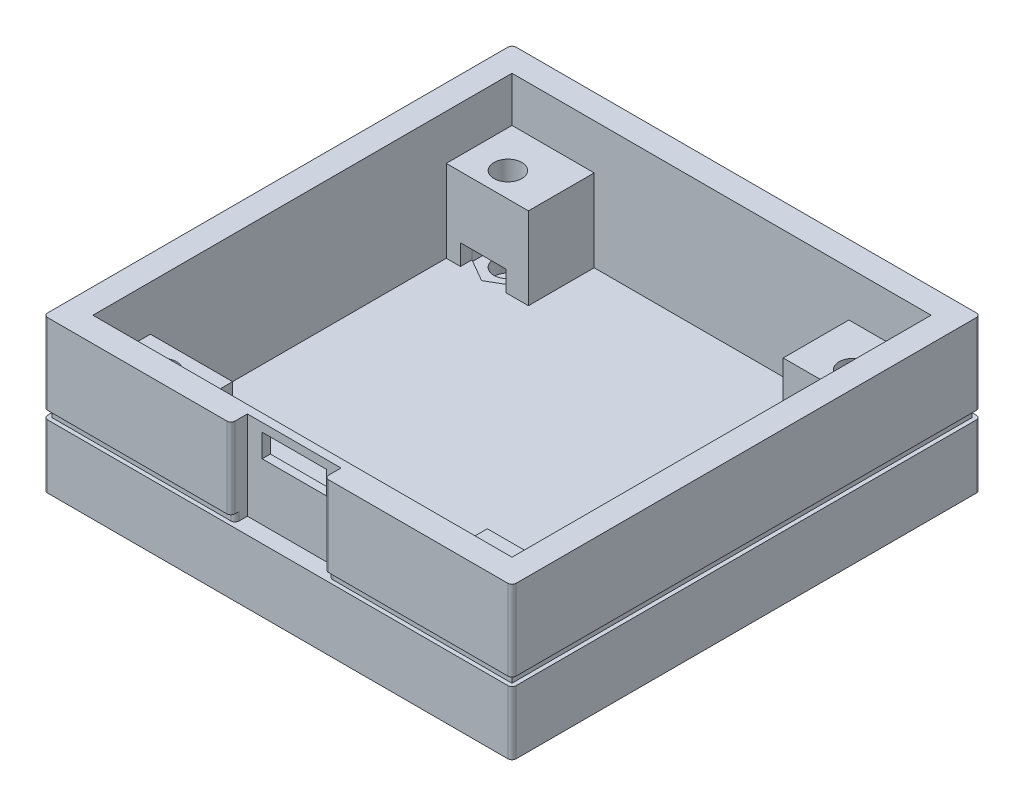
SolidWorks part; units mm, degrees
ref_plane "Plan de face" through (0, 0, 0) normal (0, 0, 1) x (1, 0, 0)
ref_plane "Plan de dessus" through (0, 0, 0) normal (0, 1, 0) x (1, 0, 0)
ref_plane "Plan de droite" through (0, 0, 0) normal (1, 0, 0) x (0, 0, -1)
sketch "Esquisse1" plane through (0, 0, 0) normal (0, 1, 0) x (1, 0, 0)
  line L1 (-30.0101, 36.8942) -> (26.9899, 36.8942)
  line L2 (-30.0101, 36.8942) -> (-30.0101, -20.1058)
  line L3 (-30.0101, -20.1058) -> (26.9899, -20.1058)
  line L4 (26.9899, 36.8942) -> (26.9899, -20.1058)
extrude "Boss.-Extru.1" add sketch "Esquisse1" along normal blind 18.5 contours L2 L3 L4 L1
sketch "Esquisse2" plane through (0, 18.5, 0) normal (0, 1, 0) x (1, 0, 0)
  line L0 (-30.0101, 36.8942) -> (26.9899, 36.8942) construction
  line L1 (-27.0101, 33.8942) -> (23.9899, 33.8942)
  line L2 (-27.0101, 33.8942) -> (-27.0101, -17.1058)
  line L3 (-27.0101, -17.1058) -> (23.9899, -17.1058)
  line L4 (23.9899, 33.8942) -> (23.9899, -17.1058)
  line L5 (-30.0101, 36.8942) -> (-30.0101, -20.1058) construction
  line L6 (26.9899, 36.8942) -> (26.9899, -20.1058) construction
  line L7 (-30.0101, -20.1058) -> (26.9899, -20.1058) construction
  dimension "D1" = 3
  dimension "D2" = 3
  dimension "D3" = 3
  dimension "D4" = 3
extrude "Enlèv. mat.-Extru.1" cut sketch "Esquisse2" against normal blind 15.5 contours L2 L3 L4 L1
sketch "Esquisse4" plane through (0, 3, 0) normal (0, 1, 0) x (1, 0, 0)
  line L1 (-17.0101, 25.8942) -> (-27.0101, 25.8942)
  line L2 (-17.0101, 25.8942) -> (-17.0101, 33.8942)
  line L3 (-17.0101, 33.8942) -> (-27.0101, 33.8942)
  line L4 (-27.0101, 25.8942) -> (-27.0101, 33.8942)
extrude "Boss.-Extru.2" add sketch "Esquisse4" along normal blind 10
sketch "Esquisse5" plane through (0, 3, 0) normal (0, 1, 0) x (1, 0, 0)
  line L1 (23.9899, 33.8942) -> (13.9899, 33.8942)
  line L2 (23.9899, 33.8942) -> (23.9899, 25.8942)
  line L3 (23.9899, 25.8942) -> (13.9899, 25.8942)
  line L4 (13.9899, 33.8942) -> (13.9899, 25.8942)
extrude "Boss.-Extru.3" add sketch "Esquisse5" along normal blind 10
sketch "Esquisse6" plane through (0, 3, 0) normal (0, 1, 0) x (1, 0, 0)
  line L1 (23.9899, -17.1058) -> (13.9899, -17.1058)
  line L2 (23.9899, -17.1058) -> (23.9899, -10.1058)
  line L3 (23.9899, -10.1058) -> (13.9899, -10.1058)
  line L4 (13.9899, -17.1058) -> (13.9899, -10.1058)
extrude "Boss.-Extru.4" add sketch "Esquisse6" along normal blind 10
sketch "Esquisse7" plane through (0, 3, 0) normal (0, 1, 0) x (1, 0, 0)
  line L1 (-17.0101, -10.1058) -> (-27.0101, -10.1058)
  line L2 (-17.0101, -10.1058) -> (-17.0101, -17.1058)
  line L3 (-17.0101, -17.1058) -> (-27.0101, -17.1058)
  line L4 (-27.0101, -10.1058) -> (-27.0101, -17.1058)
extrude "Boss.-Extru.5" add sketch "Esquisse7" along normal blind 10
sketch "Esquisse8" plane through (0, 13, 0) normal (0, 1, 0) x (1, 0, 0)
  line L0 (13.9899, -17.1058) -> (23.9899, -17.1058) construction
  line L2 (23.9899, -17.1058) -> (23.9899, -10.1058) construction
  circle A0 centre (19.4899, -13.1058) radius 1.7
  dimension "D1" = 4
  dimension "D2" = 4.5
extrude "Enlèv. mat.-Extru.2" cut sketch "Esquisse8" against normal blind 12
sketch "Esquisse9" plane through (0, 13, 0) normal (0, 1, 0) x (1, 0, 0)
  line L0 (-27.0101, -17.1058) -> (-17.0101, -17.1058) construction
  line L1 (-27.0101, -10.1058) -> (-27.0101, -17.1058) construction
  circle A0 centre (-22.5101, -13.1058) radius 1.7
  dimension "D1" = 4
  dimension "D2" = 4.5
extrude "Enlèv. mat.-Extru.3" cut sketch "Esquisse9" against normal blind 12
sketch "Esquisse16" plane through (0, 13, 0) normal (0, 1, 0) x (1, 0, 0)
  line L0 (-17.0101, 33.8942) -> (-27.0101, 33.8942) construction
  line L1 (-27.0101, 33.8942) -> (-27.0101, 25.8942) construction
  circle A0 centre (-22.5101, 28.8942) radius 1.7
  dimension "D1" = 5
  dimension "D2" = 4.5
extrude "Enlèv. mat.-Extru.9" cut sketch "Esquisse16" against normal blind 12 contours A0
sketch "Esquisse17" plane through (0, 13, 0) normal (0, 1, 0) x (1, 0, 0)
  line L0 (23.9899, 33.8942) -> (13.9899, 33.8942) construction
  line L1 (23.9899, 25.8942) -> (23.9899, 33.8942) construction
  circle A0 centre (19.4899, 28.8942) radius 1.7
  dimension "D1" = 5
  dimension "D2" = 4.5
extrude "Enlèv. mat.-Extru.10" cut sketch "Esquisse17" against normal blind 12
sketch "Esquisse21" plane through (0, 0, 20.1058) normal (0, 0, 1) x (1, 0, 0)
  line L0 (-30.0101, 0) -> (26.9899, 0) construction
  line L1 (-5.4101, 17.47) -> (2.3899, 17.47)
  line L2 (-5.4101, 17.47) -> (-5.4101, 14.67)
  line L3 (-5.4101, 14.67) -> (2.3899, 14.67)
  line L4 (2.3899, 17.47) -> (2.3899, 14.67)
  line L5 (-30.0101, 18.5) -> (-30.0101, 0) construction
  line L7 (26.9899, 18.5) -> (26.9899, 0) construction
  dimension "D1" = 14.67
  dimension "D2" = 24.6
  dimension "D3" = 24.6
extrude "Enlèv. mat.-Extru.14" cut sketch "Esquisse21" against normal blind 3
sketch "Esquisse23" plane through (0, 0, -25.8942) normal (0, 0, 1) x (1, 0, 0)
  line L0 (13.9899, 13) -> (13.9899, 3) construction
  line L5 (22.2599, 5.5) -> (16.7199, 5.5)
  line L6 (22.2599, 5.5) -> (22.2599, 3)
  line L7 (22.2599, 3) -> (16.7199, 3)
  line L8 (16.7199, 5.5) -> (16.7199, 3)
  line L9 (23.9899, 13) -> (23.9899, 3) construction
  dimension "D1" = 2.73
  dimension "D2" = 1.73
sketch "Esquisse24" plane through (0, 13, 0) normal (0, 1, 0) x (1, 0, 0)
  line L1 (19.4899, 25.6942) -> (22.2612, 27.2942)
  line L2 (22.2612, 27.2942) -> (22.2612, 30.4942)
  line L3 (22.2612, 30.4942) -> (19.4899, 32.0942)
  line L4 (19.4899, 32.0942) -> (16.7186, 30.4942)
  line L5 (16.7186, 30.4942) -> (16.7186, 27.2942)
  line L6 (16.7186, 27.2942) -> (19.4899, 25.6942)
  circle A0 centre (19.4899, 28.8942) radius 2.7713 construction
  circle A1 centre (19.4899, 28.8942) radius 1.7 construction
  dimension "D1" = 0
extrude "Enlèv. mat.-Extru.18" cut sketch "Esquisse24" against normal blind 2.7 from offset 7.5 contours L1 L2 L3 L4 L5 L6 offset against normal yes
sketch "Esquisse25" plane through (0, 13, 0) normal (0, 1, 0) x (1, 0, 0)
  line L1 (16.7186, -11.5058) -> (16.7186, -14.7058)
  line L2 (16.7186, -14.7058) -> (19.4899, -16.3058)
  line L3 (19.4899, -16.3058) -> (22.2612, -14.7058)
  line L4 (22.2612, -14.7058) -> (22.2612, -11.5058)
  line L5 (22.2612, -11.5058) -> (19.4899, -9.9058)
  line L6 (19.4899, -9.9058) -> (16.7186, -11.5058)
  circle A0 centre (19.4899, -13.1058) radius 2.7713 construction
  circle A1 centre (19.4899, -13.1058) radius 1.7 construction
  dimension "D1" = 0
extrude "Enlèv. mat.-Extru.20" cut sketch "Esquisse25" against normal blind 2.7 from offset 7.5 offset against normal yes
sketch "Esquisse26" plane through (0, 0, 10.1058) normal (0, 0, -1) x (-1, 0, 0)
  line L0 (-13.9899, 13) -> (-13.9899, 3) construction
  line L1 (-22.2599, 5.5) -> (-16.7199, 5.5)
  line L2 (-22.2599, 5.5) -> (-22.2599, 3)
  line L3 (-22.2599, 3) -> (-16.7199, 3)
  line L4 (-16.7199, 5.5) -> (-16.7199, 3)
  line L5 (-23.9899, 13) -> (-23.9899, 3) construction
  dimension "D1" = 2.73
  dimension "D2" = 1.73
extrude "Enlèv. mat.-Extru.21" cut sketch "Esquisse26" against normal blind 2.848
sketch "Esquisse27" plane through (0, 13, 0) normal (0, 1, 0) x (1, 0, 0)
  line L1 (-19.7388, 27.2942) -> (-19.7388, 30.4942)
  line L2 (-19.7388, 30.4942) -> (-22.5101, 32.0942)
  line L3 (-22.5101, 32.0942) -> (-25.2814, 30.4942)
  line L4 (-25.2814, 30.4942) -> (-25.2814, 27.2942)
  line L5 (-25.2814, 27.2942) -> (-22.5101, 25.6942)
  line L6 (-22.5101, 25.6942) -> (-19.7388, 27.2942)
  circle A0 centre (-22.5101, 28.8942) radius 2.7713 construction
  circle A1 centre (-22.5101, 28.8942) radius 1.7 construction
  dimension "D1" = 0
  dimension "D2" = 0
extrude "Enlèv. mat.-Extru.22" cut sketch "Esquisse27" against normal blind 2.7 from offset 7.5 contours L4 L5 L6 L1 L2 L3 offset against normal yes
sketch "Esquisse29" plane through (0, 13, 0) normal (0, 1, 0) x (1, 0, 0)
  line L1 (-19.7388, -11.5058) -> (-22.5101, -9.9058)
  line L2 (-22.5101, -9.9058) -> (-25.2814, -11.5058)
  line L3 (-25.2814, -11.5058) -> (-25.2814, -14.7058)
  line L4 (-25.2814, -14.7058) -> (-22.5101, -16.3058)
  line L5 (-22.5101, -16.3058) -> (-19.7388, -14.7058)
  line L6 (-19.7388, -14.7058) -> (-19.7388, -11.5058)
  circle A0 centre (-22.5101, -13.1058) radius 2.7713 construction
  circle A1 centre (-22.5101, -13.1058) radius 1.7 construction
  dimension "D1" = 0
extrude "Enlèv. mat.-Extru.24" cut sketch "Esquisse29" against normal blind 2.7 from offset 7.5 offset against normal yes
sketch "Esquisse30" plane through (0, 0, 10.1058) normal (0, 0, -1) x (-1, 0, 0)
  line L0 (17.0101, 13) -> (17.0101, 3) construction
  line L1 (25.2801, 5.5) -> (19.7401, 5.5)
  line L2 (25.2801, 5.5) -> (25.2801, 3)
  line L3 (25.2801, 3) -> (19.7401, 3)
  line L4 (19.7401, 5.5) -> (19.7401, 3)
  line L5 (27.0101, 13) -> (27.0101, 3) construction
  dimension "D1" = 2.73
  dimension "D2" = 1.73
extrude "Enlèv. mat.-Extru.26" cut sketch "Esquisse23" against normal blind 2 contours L5 L8 L7 L6
sketch "Esquisse31" plane through (0, 0, -25.8942) normal (0, 0, 1) x (1, 0, 0)
  line L0 (-27.0101, 13) -> (-27.0101, 3) construction
  line L1 (-25.2801, 5.5) -> (-19.7401, 5.5)
  line L2 (-25.2801, 5.5) -> (-25.2801, 3)
  line L3 (-25.2801, 3) -> (-19.7401, 3)
  line L4 (-19.7401, 5.5) -> (-19.7401, 3)
  line L6 (-17.0101, 13) -> (-17.0101, 3) construction
  dimension "D1" = 1.73
  dimension "D2" = 2.73
extrude "Enlèv. mat.-Extru.27" cut sketch "Esquisse31" against normal blind 2 contours L1 L4 L3 L2
extrude "Enlèv. mat.-Extru.28" cut sketch "Esquisse30" against normal blind 2 contours L1 L4 L3 L2
sketch "Esquisse32" plane through (-30.0101, 0, 0) normal (-1, 0, 0) x (0, 0, 1)
  line L0 (20.1058, 18.5) -> (20.1058, 0) construction
  line L1 (20.1058, 8.72) -> (-36.8942, 8.72)
  line L2 (20.1058, 8.72) -> (20.1058, 7.72)
  line L3 (20.1058, 7.72) -> (-36.8942, 7.72)
  line L4 (-36.8942, 8.72) -> (-36.8942, 7.72)
  line L5 (-36.8942, 18.5) -> (-36.8942, 0) construction
sketch "Esquisse33" plane through (0, 0, 20.1058) normal (0, 0, 1) x (1, 0, 0)
  line L0 (26.9899, 18.5) -> (26.9899, 0) construction
  line L1 (-30.0101, 8.72) -> (26.9899, 8.72)
  line L2 (-30.0101, 8.72) -> (-30.0101, 7.72)
  line L3 (-30.0101, 7.72) -> (26.9899, 7.72)
  line L4 (26.9899, 8.72) -> (26.9899, 7.72)
extrude "Enlèv. mat.-Extru.29" cut sketch "Esquisse32" against normal blind 0.5
extrude "Enlèv. mat.-Extru.30" cut sketch "Esquisse33" against normal blind 0.5 contours L1 L4 L3 L2
sketch "Esquisse34" plane through (26.9899, 0, 0) normal (1, 0, 0) x (0, 0, -1)
  line L0 (36.8942, 18.5) -> (36.8942, 0) construction
  line L1 (-20.1058, 7.72) -> (36.8942, 7.72)
  line L2 (-20.1058, 7.72) -> (-20.1058, 8.72)
  line L3 (-20.1058, 8.72) -> (36.8942, 8.72)
  line L4 (36.8942, 7.72) -> (36.8942, 8.72)
extrude "Enlèv. mat.-Extru.31" cut sketch "Esquisse34" against normal blind 0.5
sketch "Esquisse35" plane through (0, 0, -36.8942) normal (0, 0, -1) x (-1, 0, 0)
  line L0 (29.5101, 8.72) -> (30.0101, 8.72) construction
  line L1 (-26.9899, 7.72) -> (30.0101, 7.72)
  line L2 (-26.9899, 7.72) -> (-26.9899, 8.72)
  line L3 (-26.9899, 8.72) -> (30.0101, 8.72)
  line L4 (30.0101, 7.72) -> (30.0101, 8.72)
  line L5 (30.0101, 18.5) -> (30.0101, 8.72) construction
extrude "Enlèv. mat.-Extru.32" cut sketch "Esquisse35" against normal blind 0.5
sketch "Esquisse36" plane through (0, 0, 20.1058) normal (0, 0, 1) x (1, 0, 0)
  line L0 (-30.0101, 18.5) -> (26.9899, 18.5) construction
  line L1 (4.1899, 7.72) -> (-7.2101, 7.72)
  line L2 (4.1899, 7.72) -> (4.1899, 18.5)
  line L3 (4.1899, 18.5) -> (-7.2101, 18.5)
  line L4 (-7.2101, 7.72) -> (-7.2101, 18.5)
  line L6 (2.3899, 14.67) -> (2.3899, 17.47) construction
  line L7 (-5.4101, 17.47) -> (-5.4101, 14.67) construction
  line L9 (26.9899, 7.72) -> (-30.0101, 7.72) construction
  dimension "D1" = 1.8
  dimension "D2" = 1.8
extrude "Enlèv. mat.-Extru.33" cut sketch "Esquisse36" against normal blind 2
fillet "Congé1" radius 0.5 1 edges at (-7.2101, 13.61, 20.1058)
fillet "Congé2" radius 0.5 1 edges at (4.1899, 13.61, 20.1058)
fillet "Congé3" radius 0.5 1 edges at (-7.2101, 8.22, 19.6058)
fillet "Congé4" radius 0.5 1 edges at (4.1899, 8.22, 19.6058)
fillet "Congé5" radius 0.5 1 edges at (26.9899, 13.61, 20.1058)
fillet "Congé6" radius 0.5 1 edges at (26.9899, 3.86, 20.1058)
fillet "Congé7" radius 0.5 1 edges at (26.9899, 13.61, -36.8942)
fillet "Congé8" radius 0.5 1 edges at (26.9899, 3.86, -36.8942)
fillet "Congé9" radius 0.5 1 edges at (-30.0101, 13.61, -36.8942)
fillet "Congé10" radius 0.5 1 edges at (-30.0101, 3.86, -36.8942)
fillet "Congé11" radius 0.5 1 edges at (-30.0101, 13.61, 20.1058)
fillet "Congé12" radius 0.5 1 edges at (-30.0101, 3.86, 20.1058)
